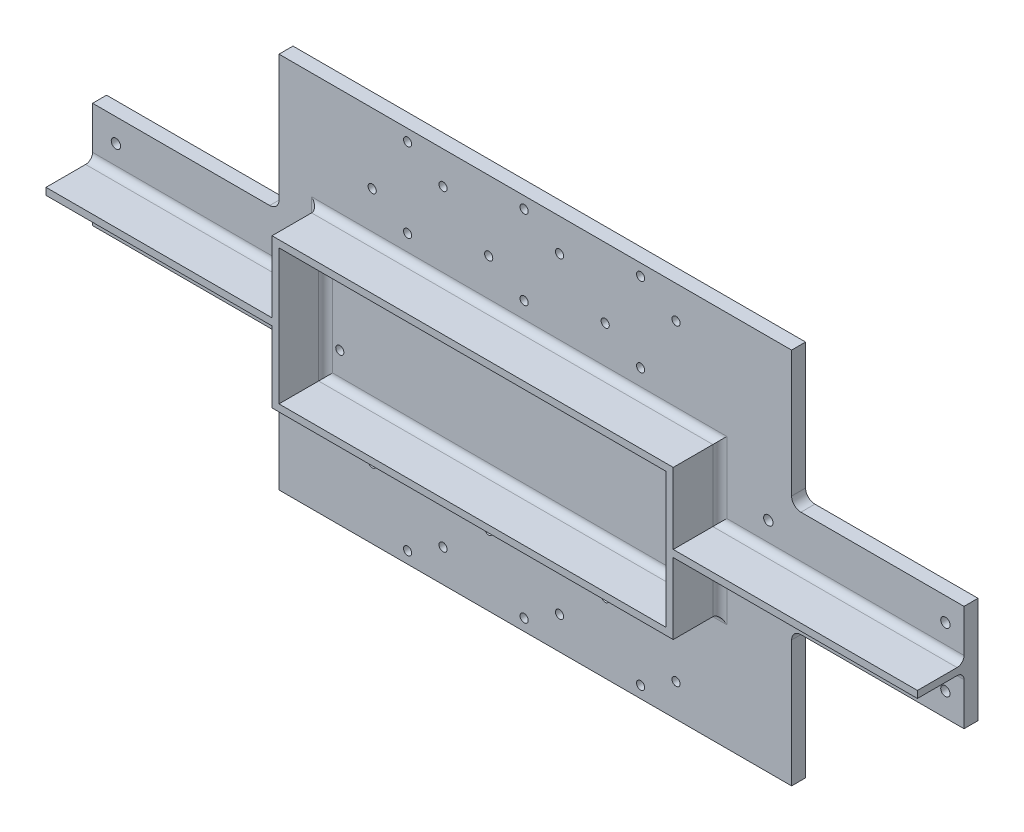
SolidWorks part; units mm, degrees
ref_plane "Top Plane" through (0, 0, 0) normal (0, 0, 1) x (1, 0, 0)
ref_plane "Right Plane" through (0, 0, 0) normal (0, 1, 0) x (1, 0, 0)
ref_plane "Front Plane" through (0, 0, 0) normal (1, 0, 0) x (0, 0, -1)
sketch "Sketch1" plane through (0, 0, 0) normal (0, 0, 1) x (1, 0, 0)
  line L0 (-187, 81) -> (187, -81) construction
  line L1 (-187, 81) -> (187, 81) construction
  line L2 (-187, 81) -> (-187, -81) construction
  line L3 (-187, -81) -> (187, -81) construction
  line L4 (187, 81) -> (187, -81) construction
  line L5 (-187, -22.75) -> (-107, -22.75) construction
  line L6 (-107, -22.75) -> (-107, -81) construction
  line L7 (113, -81) -> (113, -22.75) construction
  line L8 (113, -22.75) -> (187, -22.75) construction
  line L9 (-187, 0) -> (187, 0) construction
  line L10 (113, 22.75) -> (187, 22.75) construction
  line L11 (113, 81) -> (113, 22.75) construction
  line L12 (-107, 22.75) -> (-107, 81) construction
  line L13 (-187, 22.75) -> (-107, 22.75) construction
  line L14 (85.2, -81) -> (85.2, 81) construction
  line L15 (-93, -81) -> (-93, 81) construction
  line L16 (-187, -2.75) -> (187, -2.75) construction
  line L17 (187, 2.75) -> (-187, 2.75) construction
  text T0 "FRONT" font "Century Gothic" height in points 80
  dimension "D1" = 374
  dimension "D2" = 162
  dimension "D3" = 45.5
  dimension "D4" = 80
  dimension "D5" = 74
  dimension "D6" = 27.8
  dimension "D7" = 14
  dimension "D8" = 20
  dimension "D9" = 20
sketch "Sketch2" plane through (0, 0, 0) normal (0, 0, 1) x (1, 0, 0)
  line L0 (-187, 81) -> (-187, -81) construction
  line L1 (-187, 81) -> (187, 81) construction
  line L2 (187, 81) -> (187, -81) construction
  line L3 (-187, -81) -> (187, -81) construction
  line L4 (113, -81) -> (113, -22.75) construction
  line L5 (113, -22.75) -> (187, -22.75) construction
  line L6 (113, 22.75) -> (187, 22.75) construction
  line L7 (113, 81) -> (113, 22.75) construction
  line L8 (-107, 22.75) -> (-107, 81) construction
  line L9 (-187, 22.75) -> (-107, 22.75) construction
  line L10 (-107, -22.75) -> (-107, -81) construction
  line L11 (-187, -22.75) -> (-107, -22.75) construction
  line L12 (-187, 22.75) -> (-187, -22.75)
  line L13 (-107, 81) -> (113, 81)
  line L14 (187, 22.75) -> (187, -22.75)
  line L15 (-107, -81) -> (113, -81)
  line L16 (113, -81) -> (113, -22.75)
  line L17 (113, -22.75) -> (187, -22.75)
  line L18 (113, 22.75) -> (187, 22.75)
  line L19 (113, 81) -> (113, 22.75)
  line L20 (-107, 22.75) -> (-107, 81)
  line L21 (-187, 22.75) -> (-107, 22.75)
  line L22 (-107, -22.75) -> (-107, -81)
  line L23 (-187, -22.75) -> (-107, -22.75)
extrude "Boss-Extrude1" add sketch "Sketch2" along normal mid plane 6
sketch "Sketch3" plane through (0, 0, 3) normal (0, 0, 1) x (1, 0, 0)
  line L0 (-187, -1.5) -> (-90, -1.5)
  line L1 (-187, 81) -> (-187, -81) construction
  line L2 (187, 81) -> (187, -81) construction
  line L3 (-187, 0) -> (187, 0) construction
  line L4 (-187, 0) -> (187, 0) construction
  line L5 (-187, 1.5) -> (-90, 1.5)
  line L6 (-90, 32) -> (-90, 1.5)
  line L7 (-90, -32) -> (82.2, -32)
  line L8 (82.2, -32) -> (82.2, -1.5)
  line L9 (85.2, -81) -> (85.2, 81) construction
  line L10 (-93, -81) -> (-93, 81) construction
  line L11 (-87, 29) -> (-87, -29)
  line L12 (-87, -29) -> (79.2, -29)
  line L13 (79.2, -29) -> (79.2, 29)
  line L14 (-90, -2.5) -> (-90, -32) construction
  line L15 (-87, -2.5) -> (-87, -29) construction
  line L16 (82.2, -32) -> (82.2, -2.5) construction
  line L17 (79.2, -29) -> (79.2, -2.5) construction
  line L18 (-87, 29) -> (79.2, 29)
  line L19 (-90, 32) -> (82.2, 32)
  line L20 (82.2, 1.5) -> (187, 1.5)
  line L21 (82.2, -1.5) -> (187, -1.5)
  line L22 (82.2, 1.5) -> (82.2, 32)
  line L23 (-90, -1.5) -> (-90, -32)
  line L24 (187, -1.5) -> (187, 1.5)
  line L25 (-187, -1.5) -> (-187, 1.5)
  point P34 (-87, 0)
  point P35 (79.2, 0)
  dimension "D1" = 3
  dimension "D2" = 3
  dimension "D3" = 3
  dimension "D4" = 64
  dimension "D5" = 3
extrude "Boss-Extrude2" add sketch "Sketch3" along normal blind 20
sketch "Sketch4" plane through (0, 0, 3) normal (0, 0, 1) x (1, 0, 0)
  line L0 (-17, -67) -> (13.4, -67) construction
  line L1 (-67, -67) -> (-36.6, -67) construction
  line L2 (-67, -67) -> (-67, -51) construction
  line L3 (-67, -51) -> (-36.6, -51) construction
  line L4 (-36.6, -67) -> (-36.6, -51) construction
  line L5 (-17, -67) -> (-17, -51) construction
  line L6 (-17, -51) -> (13.4, -51) construction
  line L7 (13.4, -67) -> (13.4, -51) construction
  line L8 (33, -67) -> (63.4, -67) construction
  line L9 (33, -67) -> (33, -51) construction
  line L10 (33, -51) -> (63.4, -51) construction
  line L11 (63.4, -67) -> (63.4, -51) construction
  line L12 (-36.6, -67) -> (13.4, -67) construction
  line L13 (-107, -22.75) -> (-107, -81) construction
  line L15 (-187, -81) -> (187, -81) construction
  line L16 (-187, 0) -> (187, 0) construction
  line L17 (-187, 0) -> (187, 0) construction
  line L18 (-36.6, 67) -> (13.4, 67) construction
  line L19 (63.4, 67) -> (63.4, 51) construction
  line L20 (33, 51) -> (63.4, 51) construction
  line L21 (33, 67) -> (33, 51) construction
  line L22 (33, 67) -> (63.4, 67) construction
  line L23 (13.4, 67) -> (13.4, 51) construction
  line L24 (-17, 51) -> (13.4, 51) construction
  line L25 (-17, 67) -> (-17, 51) construction
  line L26 (-36.6, 67) -> (-36.6, 51) construction
  line L27 (-67, 51) -> (-36.6, 51) construction
  line L28 (-67, 67) -> (-67, 51) construction
  line L29 (-67, 67) -> (-36.6, 67) construction
  line L30 (-17, 67) -> (13.4, 67) construction
  circle A0 centre (-36.6, -67) radius 1.75
  circle A1 centre (-67, -51) radius 1.75
  circle A2 centre (13.4, -67) radius 1.75
  circle A3 centre (-17, -51) radius 1.75
  circle A4 centre (63.4, -67) radius 1.75
  circle A5 centre (33, -51) radius 1.75
  circle A6 centre (33, 51) radius 1.75
  circle A7 centre (63.4, 67) radius 1.75
  circle A8 centre (-17, 51) radius 1.75
  circle A9 centre (13.4, 67) radius 1.75
  circle A10 centre (-67, 51) radius 1.75
  circle A11 centre (-36.6, 67) radius 1.75
  dimension "D3" = 3.5
  dimension "D1" = 16
  dimension "D2" = 30.4
  dimension "D5" = 50
  dimension "D6" = 40
  dimension "D7" = 14
  dimension "D4" = 3
extrude "Cut-Extrude1" cut sketch "Sketch4" against normal through all
fillet "Fillet1" radius 4 4 edges at (-107, 22.75, 0) (-107, -22.75, 0) (113, -22.75, 0) (113, 22.75, 0)
fillet "Fillet2" radius 3 14 edges at (79.2, 0, 3) (-3.9, -29, 3) (-87, 0, 3) (-3.9, 29, 3) (-90, 16.75, 3) (-138.5, 1.5, 3) (-138.5, -1.5, 3) (-90, -16.75, 3) (-3.9, -32, 3) (82.2, -16.75, 3) (134.6, -1.5, 3) (-3.9, 32, 3) (134.6, 1.5, 3) (82.2, 16.75, 3)
sketch "Sketch5" plane through (0, 0, -3) normal (0, 0, -1) x (-1, 0, 0)
  circle A0 centre (-103, -12.75) radius 2 construction
  circle A1 centre (-103, 12.75) radius 2 construction
  circle A2 centre (-179, 12.75) radius 2 construction
  circle A3 centre (-179, -12.75) radius 2 construction
  circle A4 centre (177, 12.75) radius 2 construction
  circle A5 centre (177, -12.75) radius 2 construction
  circle A6 centre (101, -12.75) radius 2 construction
  circle A7 centre (101, 12.75) radius 2 construction
  circle A8 centre (-103, -12.75) radius 2
  circle A9 centre (-103, 12.75) radius 2
  circle A10 centre (-179, 12.75) radius 2
  circle A11 centre (-179, -12.75) radius 2
  circle A12 centre (177, 12.75) radius 2
  circle A13 centre (177, -12.75) radius 2
  circle A14 centre (101, -12.75) radius 2
  circle A15 centre (101, 12.75) radius 2
extrude "Cut-Extrude2" cut sketch "Sketch5" against normal up to next
sketch "Sketch6" plane through (0, 0, 3) normal (0, 0, 1) x (1, 0, 0)
  line L0 (-67, -67) -> (-36.6, -51) construction
  line L1 (-51.8, -76) -> (-51.8, -42) construction
  line L2 (-67, -59) -> (-36.6, -59) construction
  line L3 (-67, -67) -> (-67, -51) construction
  line L4 (-36.6, -67) -> (-36.6, -51) construction
  line L5 (-1.8, -76) -> (-1.8, -42) construction
  line L6 (48.2, -76) -> (48.2, -42) construction
  line L7 (-51.8, -59) -> (-1.8, -59) construction
  line L8 (-187, 0) -> (187, 0) construction
  line L9 (-187, 0) -> (187, 0) construction
  line L10 (-51.8, 59) -> (-1.8, 59) construction
  line L11 (48.2, 76) -> (48.2, 42) construction
  line L12 (-1.8, 76) -> (-1.8, 42) construction
  line L13 (-67, 59) -> (-36.6, 59) construction
  line L14 (-51.8, 76) -> (-51.8, 42) construction
  line L15 (-67, 67) -> (-36.6, 51) construction
  circle A0 centre (-51.8, -76) radius 1.75
  circle A1 centre (-51.8, -42) radius 1.75
  circle A2 centre (-1.8, -76) radius 1.75
  circle A3 centre (-1.8, -42) radius 1.75
  circle A4 centre (48.2, -76) radius 1.75
  circle A5 centre (48.2, -42) radius 1.75
  circle A6 centre (48.2, 42) radius 1.75
  circle A7 centre (48.2, 76) radius 1.75
  circle A8 centre (-1.8, 42) radius 1.75
  circle A9 centre (-1.8, 76) radius 1.75
  circle A10 centre (-51.8, 42) radius 1.75
  circle A11 centre (-51.8, 76) radius 1.75
  point P4 (-51.8, -59)
  point P17 (-1.8, -59)
  point P22 (48.2, -59)
  point P47 (48.2, 59)
  dimension "D1" = 3.5
  dimension "D2" = 34
  dimension "D4" = 50
  dimension "D3" = 3
extrude "Cut-Extrude3" cut sketch "Sketch6" against normal through all
sketch "Sketch8" plane through (0, 0, 3) normal (0, 0, 1) x (1, 0, 0)
  line L0 (-80.9, -16) -> (73.1, 16) construction
  line L1 (-80.9, -16) -> (73.1, -16) construction
  line L2 (-80.9, -16) -> (-80.9, 16) construction
  line L3 (-80.9, 16) -> (73.1, 16) construction
  line L4 (73.1, -16) -> (73.1, 16) construction
  line L5 (-187, 0) -> (187, 0) construction
  line L6 (-187, 0) -> (187, 0) construction
  line L7 (-3.9, -21.9049) -> (-3.9, 21.9049) construction
  line L8 (-93, -81) -> (85.2, 81) construction
  circle A0 centre (-80.9, -16) radius 1.75
  circle A1 centre (-80.9, 16) radius 1.75
  circle A2 centre (73.1, 16) radius 1.75
  circle A3 centre (73.1, -16) radius 1.75
  point P7 (-3.9, 0)
  dimension "D3" = 3.5
  dimension "D1" = 32
  dimension "D2" = 154
extrude "Cut-Extrude5" cut sketch "Sketch8" against normal through all
